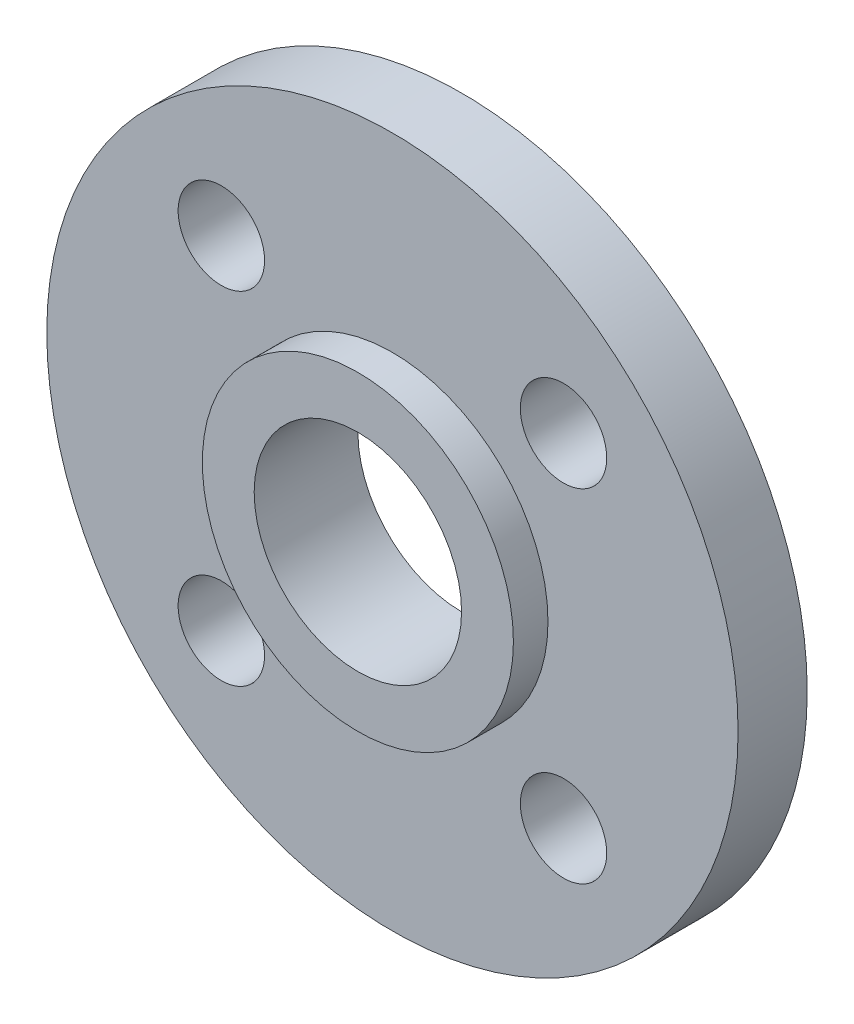
SolidWorks part; units mm, degrees
material "1060-H12"
ref_plane "前视基准面" through (0, 0, 0) normal (0, 0, 1) x (1, 0, 0)
ref_plane "上视基准面" through (0, 0, 0) normal (0, 1, 0) x (1, 0, 0)
ref_plane "右视基准面" through (0, 0, 0) normal (1, 0, 0) x (0, 0, -1)
sketch "草图1" plane through (0, 0, 0) normal (0, 0, 1) x (1, 0, 0)
  line L0 (-4.9497, 4.9497) -> (4.9497, 4.9497) construction
  line L1 (4.9497, 4.9497) -> (4.9497, -4.9497) construction
  circle A0 centre (0, 0) radius 10
  circle A1 centre (-4.9497, 4.9497) radius 1.25
  circle A2 centre (4.9497, 4.9497) radius 1.25
  circle A3 centre (4.9497, -4.9497) radius 1.25
  circle A4 centre (-4.9497, -4.9497) radius 1.25
  circle A5 centre (0, 0) radius 7 construction
  circle A6 centre (0, 0) radius 3
  dimension "D1" = 20
  dimension "D2" = 2.5
  dimension "D3" = 6
  dimension "D4" = 14
extrude "凸台-拉伸1" add sketch "草图1" along normal blind 2
cosmetic thread "装饰螺纹线1" parameters "D2"=3
cosmetic thread "装饰螺纹线3" parameters "D2"=3
cosmetic thread "装饰螺纹线4" parameters "D2"=3
sketch "草图2" plane through (0, 0, 2) normal (0, 0, 1) x (1, 0, 0)
  circle A0 centre (0, 0) radius 4.5
  circle A1 centre (0, 0) radius 3
  dimension "D1" = 9
  dimension "D2" = 6
extrude "凸台-拉伸2" add sketch "草图2" along normal blind 1
